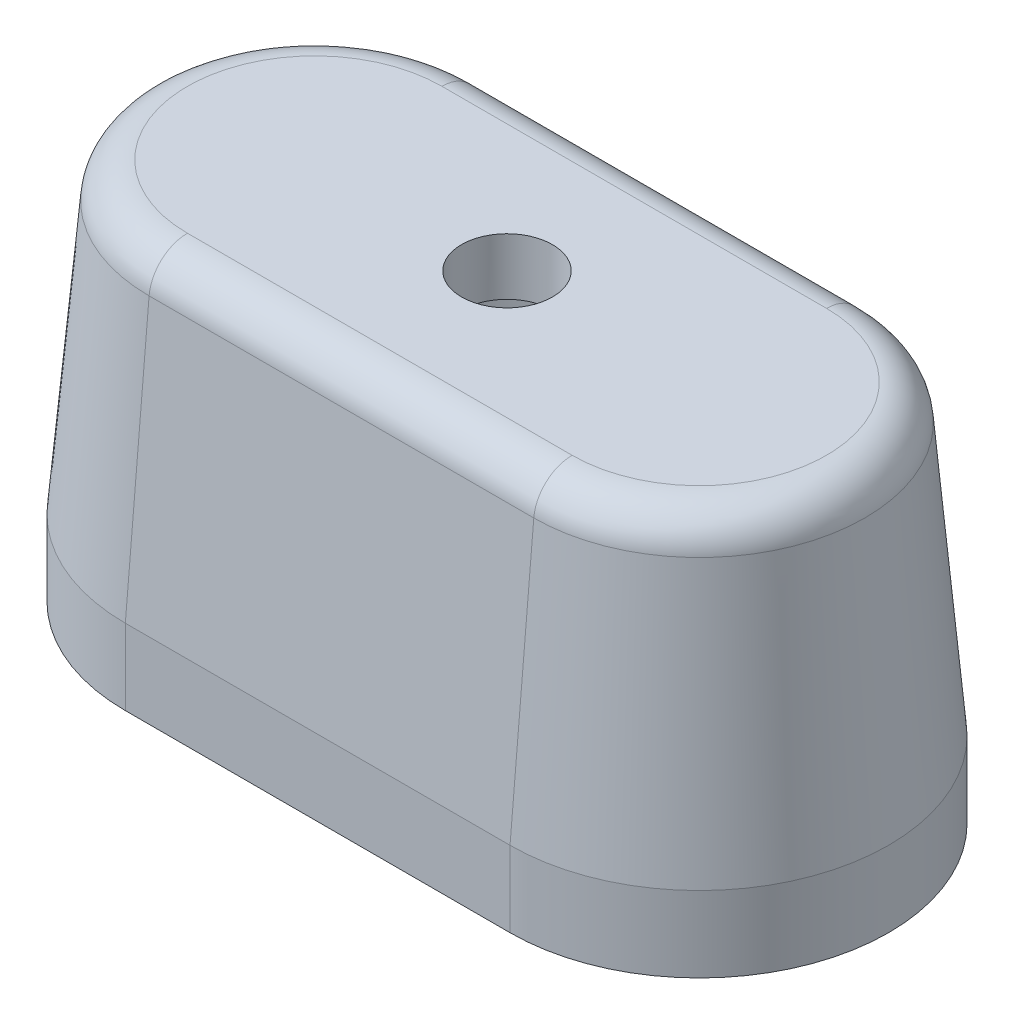
SolidWorks part; units mm, degrees
ref_plane "Front Plane" through (0, 0, 0) normal (0, 0, 1) x (1, 0, 0)
ref_plane "Top Plane" through (0, 0, 0) normal (0, 1, 0) x (1, 0, 0)
ref_plane "Right Plane" through (0, 0, 0) normal (1, 0, 0) x (0, 0, -1)
sketch "Sketch1" plane through (0, 0, 0) normal (0, 1, 0) x (1, 0, 0)
  line L1 (-51.435, -26.035) -> (51.435, -26.035)
  line L2 (-51.435, -26.035) -> (-51.435, 26.035)
  line L3 (-51.435, 26.035) -> (51.435, 26.035)
  line L4 (51.435, -26.035) -> (51.435, 26.035)
  line L5 (-51.435, -26.035) -> (51.435, 26.035) construction
  line L6 (-51.435, 26.035) -> (51.435, -26.035) construction
  point P0 (0, 0)
  dimension "D1" = 52.07
  dimension "D2" = 102.87
extrude "Boss-Extrude2" add sketch "Sketch1" along normal blind 10
sketch "Sketch3" plane through (0, 10, 0) normal (0, 1, 0) x (1, 0, 0)
  line L0 (-25.4, 0) -> (25.4, 0) construction
  line L1 (-25.4, 25) -> (25.4, 25)
  line L2 (-25.4, -25) -> (25.4, -25)
  arc A0 (-25.4, 25) -> (-25.4, -25) centre (-25.4, 0) ccw
  arc A1 (25.4, -25) -> (25.4, 25) centre (25.4, 0) ccw
  point P3 (0, 0)
  dimension "D1" = 50.8
  dimension "D2" = 0
  dimension "D3" = 50
extrude "Boss-Extrude3" add sketch "Sketch3" along normal blind 40.5 draft 5
sketch "Sketch4" plane through (0, 0, 0) normal (0, -1, 0) x (1, 0, 0)
  circle A0 centre (0, 0) radius 21.25
  dimension "D1" = 42.5
extrude "Cut-Extrude2" cut sketch "Sketch4" against normal blind 43 contours A0
fillet "Fillet1" radius 5.08 4 edges at (0, 50.5, 21.4567) (46.8567, 50.5, 0) (-46.8567, 50.5, 0) (0, 50.5, -21.4567)
sketch "Sketch5" plane through (0, 50.5, 0) normal (0, 1, 0) x (1, 0, 0)
  circle A0 centre (0, 0) radius 6
  dimension "D1" = 12
extrude "Cut-Extrude3" cut sketch "Sketch5" against normal through all
sketch "Sketch6" plane through (0, 10, 0) normal (0, 1, 0) x (1, 0, 0)
  line L0 (-25.4, 0) -> (25.4, 0) construction
  line L1 (-25.4, 25) -> (25.4, 25)
  line L2 (-25.4, -25) -> (25.4, -25)
  line L3 (25.4, 25) -> (-25.4, 25) construction
  arc A0 (-25.4, 25) -> (-25.4, -25) centre (-25.4, 0) ccw
  arc A1 (25.4, -25) -> (25.4, 25) centre (25.4, 0) ccw
  point P3 (0, 0)
  dimension "D1" = 50.8
  dimension "D2" = 0
  dimension "D3" = 0
extrude "Cut-Extrude4" cut sketch "Sketch6" against normal through all flip side to cut
